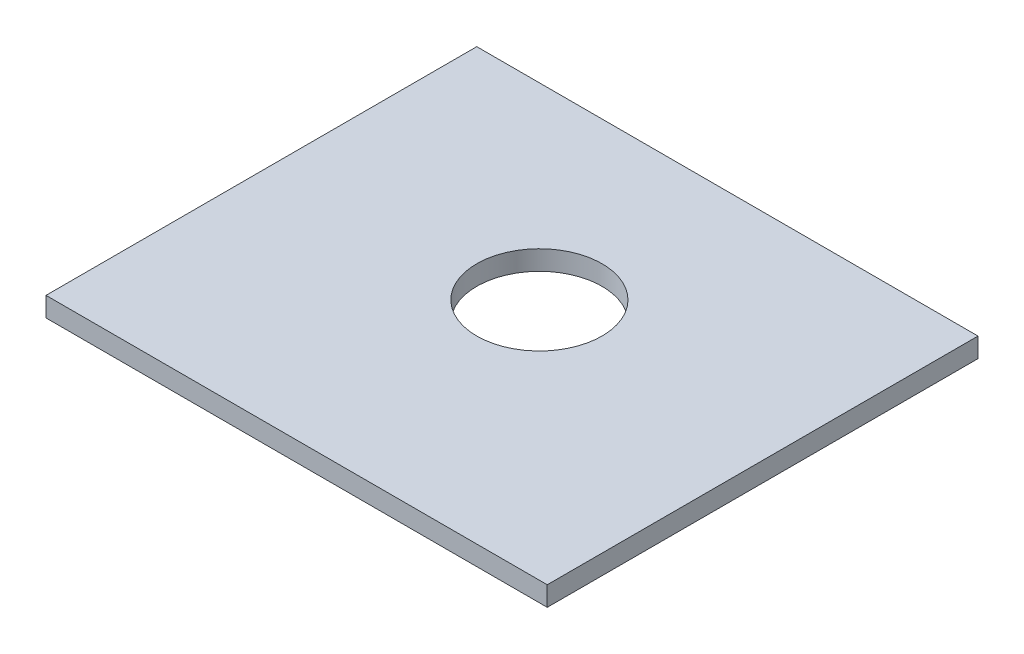
SolidWorks part; units mm, degrees
ref_plane "Front Plane" through (0, 0, 0) normal (0, 0, 1) x (1, 0, 0)
ref_plane "Top Plane" through (0, 0, 0) normal (0, 1, 0) x (1, 0, 0)
ref_plane "Right Plane" through (0, 0, 0) normal (1, 0, 0) x (0, 0, -1)
sketch "Sketch1" plane through (0, 0, 0) normal (0, 1, 0) x (1, 0, 0)
  line L1 (40.64, -34.925) -> (-40.64, -34.925)
  line L2 (40.64, -34.925) -> (40.64, 34.925)
  line L3 (40.64, 34.925) -> (-40.64, 34.925)
  line L4 (-40.64, -34.925) -> (-40.64, 34.925)
  line L5 (40.64, -34.925) -> (-40.64, 34.925) construction
  line L6 (40.64, 34.925) -> (-40.64, -34.925) construction
  point P0 (0, 0)
  dimension "D1" = 81.28
  dimension "D2" = 69.85
extrude "Boss-Extrude1" add sketch "Sketch1" along normal blind 3.175
sketch "Sketch2" plane through (0, 3.175, 0) normal (0, 1, 0) x (1, 0, 0)
  line L2 (40.64, 34.925) -> (-40.64, 34.925) construction
  circle A0 centre (0, 4.445) radius 10.16
  point P2 (0, 0)
  point P5 (0, 0)
  point P6 (0, 0)
  point P7 (27.487, 0)
  point P9 (19.4887, 0)
  point P10 (-12.042, 0)
  point P11 (0, -16.5922)
  dimension "D1" = 20.32
  dimension "D2" = 30.48
extrude "Cut-Extrude1" cut sketch "Sketch2" against normal up to next
